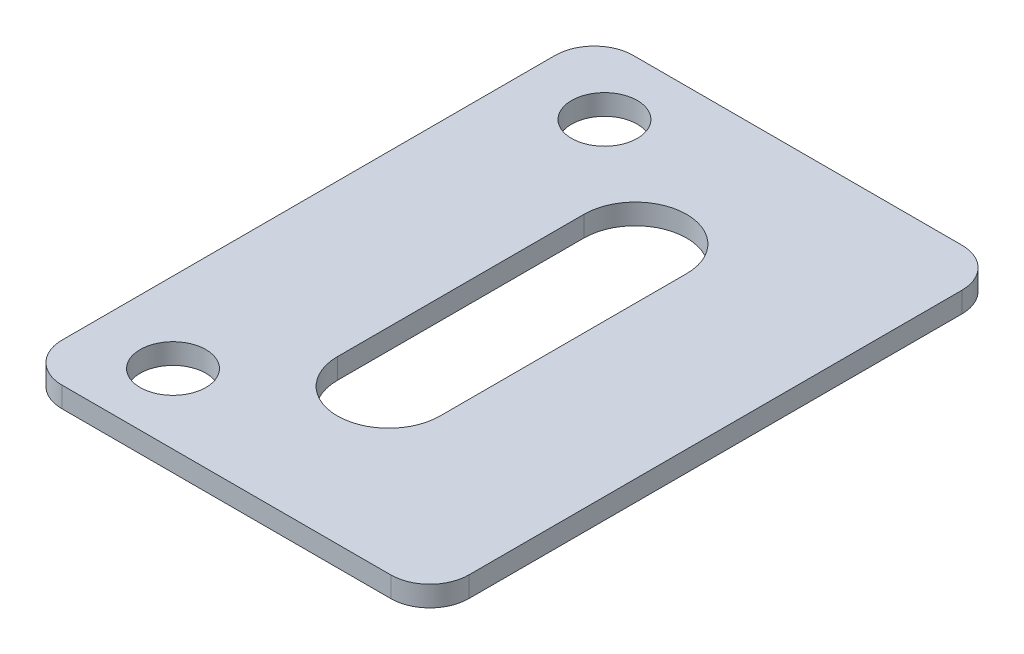
SolidWorks part; units mm, degrees
ref_plane "Front" through (0, 0, 0) normal (0, 0, 1) x (1, 0, 0)
ref_plane "Top" through (0, 0, 0) normal (0, 1, 0) x (1, 0, 0)
ref_plane "Right" through (0, 0, 0) normal (1, 0, 0) x (0, 0, -1)
sketch "Sketch1" plane through (0, 0, 0) normal (0, 1, 0) x (1, 0, 0)
  line L1 (-10, -14) -> (10, -14)
  line L2 (-10, -14) -> (-10, 14)
  line L3 (-10, 14) -> (10, 14)
  line L4 (10, -14) -> (10, 14)
  line L5 (-10, -14) -> (10, 14) construction
  line L6 (-10, 14) -> (10, -14) construction
  point P0 (0, 0)
  dimension "D1" = 20
  dimension "D2" = 28
extrude "Boss-Extrude1" add sketch "Sketch1" along normal blind 1
fillet "Fillet1" radius 2 4 edges at (-10, 0.5, 14) (-10, 0.5, -14) (10, 0.5, -14) (10, 0.5, 14)
sketch "Sketch2" plane through (0, 1, 0) normal (0, 1, 0) x (1, 0, 0)
  line L22 (-12.7368, -15.2814) -> (12.7368, -15.2814)
  line L23 (-12.7368, -15.2814) -> (-12.7368, 15.2814)
  line L24 (-12.7368, 15.2814) -> (12.7368, 15.2814)
  line L25 (-8, -13.9) -> (8, -13.9)
  line L26 (9.9, -12) -> (9.9, 12)
  line L27 (-9.9, 12) -> (-9.9, -12)
  line L28 (8, 13.9) -> (-8, 13.9)
  line L29 (-8, -13.9) -> (8, -13.9)
  line L30 (9.9, -12) -> (9.9, 12)
  line L31 (-9.9, 12) -> (-9.9, -12)
  line L32 (8, 13.9) -> (-8, 13.9)
  line L33 (12.7368, -15.2814) -> (12.7368, 15.2814)
  line L34 (-12.7368, -15.2814) -> (12.7368, 15.2814) construction
  line L35 (-12.7368, 15.2814) -> (12.7368, -15.2814) construction
  arc A19 (-9.9, -12) -> (-8, -13.9) centre (-8, -12) ccw
  arc A20 (8, -13.9) -> (9.9, -12) centre (8, -12) ccw
  arc A21 (9.9, 12) -> (8, 13.9) centre (8, 12) ccw
  arc A22 (-8, 13.9) -> (-9.9, 12) centre (-8, 12) ccw
  arc A23 (-9.9, -12) -> (-8, -13.9) centre (-8, -12) ccw
  arc A24 (8, -13.9) -> (9.9, -12) centre (8, -12) ccw
  arc A25 (9.9, 12) -> (8, 13.9) centre (8, 12) ccw
  arc A26 (-8, 13.9) -> (-9.9, 12) centre (-8, 12) ccw
  point P0 (0, 0)
  dimension "D1" = 0.1
extrude "Cut-Extrude1" cut sketch "Sketch2" against normal through all
sketch "Sketch3" plane through (0, 0, 0) normal (0, -1, 0) x (-1, 0, 0)
  circle A0 centre (6, -10.5) radius 1.6
  circle A1 centre (6, 10.5) radius 1.6
  dimension "D1" = 3.2
extrude "Cut-Extrude2" cut sketch "Sketch3" against normal through all
sketch "Sketch4" plane through (0, 1, 0) normal (0, 1, 0) x (1, 0, 0)
  line L0 (0, 6) -> (0, -6) construction
  line L1 (2.5, 6) -> (2.5, -6)
  line L2 (-2.5, 6) -> (-2.5, -6)
  arc A0 (2.5, 6) -> (-2.5, 6) centre (0, 6) ccw
  arc A1 (-2.5, -6) -> (2.5, -6) centre (0, -6) ccw
  point P3 (0, 0)
  dimension "D1" = 2.5
  dimension "D2" = 12
  dimension "D3" = 0
extrude "Cut-Extrude3" cut sketch "Sketch4" against normal blind 10
